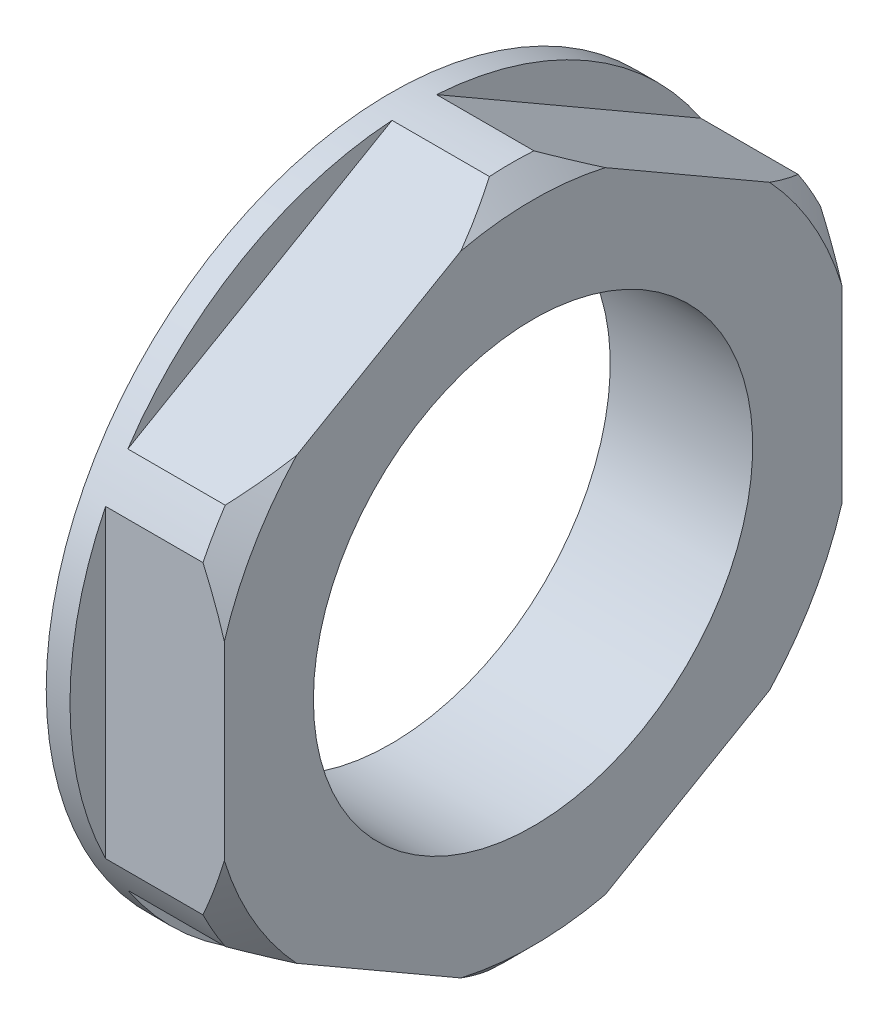
SolidWorks part; units mm, degrees
ref_plane "Спереди" through (0, 0, 0) normal (0, 0, 1) x (1, 0, 0)
ref_plane "Сверху" through (0, 0, 0) normal (0, 1, 0) x (1, 0, 0)
ref_plane "Справа" through (0, 0, 0) normal (1, 0, 0) x (0, 0, -1)
sketch "Эскиз1" plane through (0, 0, 0) normal (1, 0, 0) x (0, 0, -1)
  line L0 (0, 15.0111) -> (0, -15.0111) construction
  line L1 (0, 15.0111) -> (-13, 7.5056)
  line L2 (-13, 7.5056) -> (-13, -7.5056)
  line L3 (-13, -7.5056) -> (0, -15.0111)
  line L4 (0, -15.0111) -> (13, -7.5056)
  line L5 (13, -7.5056) -> (13, 7.5056)
  line L6 (13, 7.5056) -> (0, 15.0111)
  circle A0 centre (0, 0) radius 15.0111
  dimension "D1" = 120
  dimension "D2" = 26
extrude "Вытянуть1" add sketch "Эскиз1" along normal blind 6 contours L0 L1 L2 L3 | L6 L0 L4 L5
sketch "Эскиз3" plane through (0, 0, 0) normal (-1, 0, 0) x (0, 0, 1)
  circle A0 centre (0, 0) radius 14.5
  dimension "D1" = 29
extrude "Вытянуть2" add sketch "Эскиз3" against normal blind 1
sketch "Эскиз4" plane through (0, 0, 0) normal (-1, 0, 0) x (0, 0, 1)
  circle A0 centre (0, 0) radius 15.0111
  circle A1 centre (0, 0) radius 14.5
  arc A2 (12.0621, 8.047) -> (0.9379, 14.4696) centre (0, 0) ccw construction
extrude "Вырез-Вытянуть1" cut sketch "Эскиз4" against normal through all
sketch "Эскиз5" plane through (0, 0, 0) normal (-1, 0, 0) x (0, 0, 1)
  circle A0 centre (0, 0) radius 9.25
  dimension "D1" = 18.5
extrude "Вырез-Вытянуть2" cut sketch "Эскиз5" against normal through all
ref_axis "Ось1" through (6, 0, 0) along (-1, 0, 0)
sketch "Эскиз6" plane through (0, 0, 0) normal (0, 0, 1) x (1, 0, 0)
  line L0 (4.5, 15.1) -> (6, 13.6)
  line L1 (6, 14.4696) -> (6, 8.047) construction
  line L2 (6, 13.6) -> (6, 15.1)
  line L3 (6, 15.1) -> (4.5, 15.1)
  line L4 (6, 0) -> (0, 0) construction
  dimension "D1" = 15.1
  dimension "D2" = 1.5
  dimension "D3" = 45
revolve "Вырез-Повернуть1" cut sketch "Эскиз6" angle 360 about axis through (6, 0, 0) along (-1, 0, 0)
